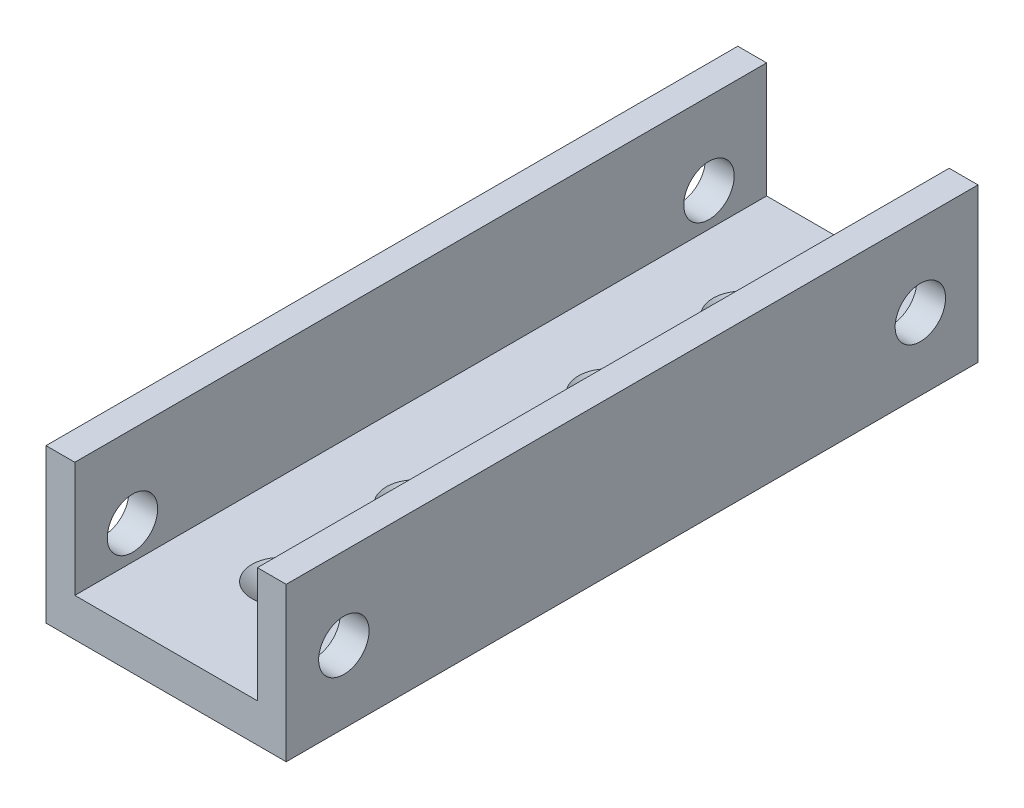
SolidWorks part; units mm, degrees
ref_plane "Front Plane" through (0, 0, 0) normal (0, 0, 1) x (1, 0, 0)
ref_plane "Top Plane" through (0, 0, 0) normal (0, 1, 0) x (1, 0, 0)
ref_plane "Right Plane" through (0, 0, 0) normal (1, 0, 0) x (0, 0, -1)
sketch "Sketch1" plane through (0, 0, 0) normal (0, 0, 1) x (1, 0, 0)
  line L0 (-19.8438, 25.4) -> (-19.8437, 0)
  line L1 (-19.8437, 0) -> (19.8437, 0)
  line L2 (19.8437, 0) -> (19.8438, 25.4)
  line L3 (19.8438, 25.4) -> (15.0812, 25.4)
  line L4 (15.0812, 25.4) -> (15.0812, 6.35)
  line L5 (15.0812, 6.35) -> (-15.0812, 6.35)
  line L6 (-15.0812, 6.35) -> (-15.0813, 25.4)
  line L7 (-15.0813, 25.4) -> (-19.8438, 25.4)
  point P2 (0, 0)
  dimension "D1" = 30.1625
  dimension "D2" = 6.35
  dimension "D3" = 4.7625
  dimension "D4" = 4.7625
  dimension "D5" = 19.05
extrude "Boss-Extrude1" add sketch "Sketch1" along normal mid plane 114.3 contours L7 L0 L1 L2 L3 L4 L5 L6
sketch "Sketch3" plane through (0, 6.35, 0) normal (0, 1, 0) x (1, 0, 0)
  line L0 (-15.0812, 0) -> (15.0813, 0) construction
  line L1 (-15.0812, -57.15) -> (-15.0812, 57.15) construction
  line L2 (15.0813, -57.15) -> (15.0813, 57.15) construction
  point P6 (0, 38.1)
  point P7 (0, 15.875)
  point P8 (0, -15.875)
  point P10 (0, -38.1)
  dimension "D1" = 22.225
  dimension "D2" = 38.1
  dimension "D3" = 22.225
  dimension "D4" = 31.75
hole_wizard "CSK for #10 Flat Head Machine Screw (100)1" positions "Sketch4" profile "Sketch5" countersink size "#10" standard "ANSI Inch" end condition through all
sketch "Sketch4" plane through (0, 6.35, 0) normal (0, 1, 0) x (1, 0, 0)
  point P0 (0, 15.875)
  point P3 (0, 38.1)
  point P6 (0, -15.875)
  point P9 (0, -38.1)
sketch "Sketch5" plane through (0, 6.35, -15.875) normal (1, 0, 0) x (0, 0, 1)
  line L0 (0, 0) -> (0, 6.35)
  line L1 (0, 6.35) -> (2.5527, 6.35)
  line L2 (2.5527, 6.35) -> (2.5527, 1.9608)
  line L3 (2.5527, 1.9608) -> (4.8895, 0)
  line L5 (4.8895, 0) -> (0, 0)
  line L6 (-2.5527, 1.9608) -> (-4.8895, 0) construction
  line L11 (0, -6.35) -> (0, 107.95) construction
  dimension "Thru Hole Dia." = 5.1054
  dimension "Thru Hole Depth" = 6.35
  dimension "Near C'Sink Dia." = 9.779
  dimension "Near C'Sink Angle" = 100
sketch "Sketch6" plane through (19.8437, 0, 0) normal (1, 0, 0) x (0, 0, -1)
  line L0 (-57.15, 12.7) -> (57.15, 12.7) construction
  line L1 (-57.15, 0) -> (-57.15, 25.4) construction
  line L2 (57.15, 0) -> (57.15, 25.4) construction
  line L3 (-57.15, 6.35) -> (57.15, 6.35) construction
  line L4 (-57.15, 6.35) -> (57.15, 6.35) construction
  line L7 (57.15, 0) -> (57.15, 25.4)
  line L8 (57.15, 25.4) -> (-57.15, 25.4)
  line L9 (-57.15, 25.4) -> (-57.15, 0)
  line L10 (-57.15, 0) -> (57.15, 0)
  line L11 (57.15, 0) -> (57.15, 25.4)
  line L12 (57.15, 25.4) -> (-57.15, 25.4)
  line L13 (-57.15, 25.4) -> (-57.15, 0)
  line L14 (-57.15, 0) -> (57.15, 0)
  circle A0 centre (-47.625, 11.9062) radius 4.1672
  circle A1 centre (47.625, 11.9062) radius 4.1672
  dimension "D1" = 8.3344
  dimension "D3" = 5.5562
  dimension "D4" = 9.525
  dimension "D5" = 9.525
  dimension "D2" = 0
extrude "Cut-Extrude2" cut sketch "Sketch6" against normal through all flip side to cut
